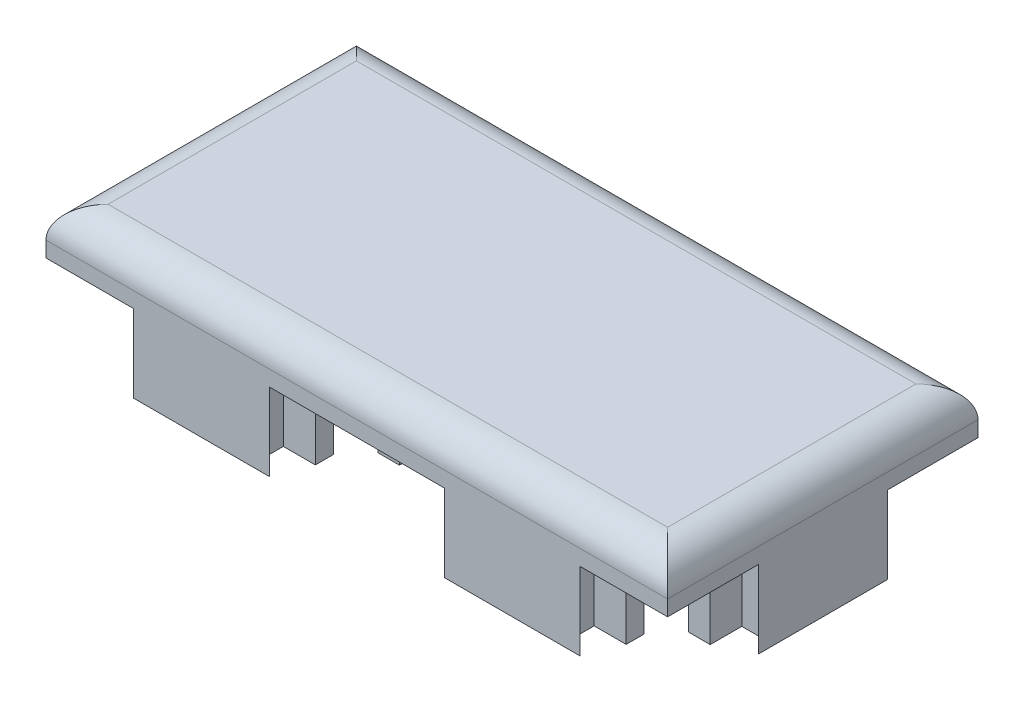
SolidWorks part; units mm, degrees
ref_plane "Alzado" through (0, 0, 0) normal (0, 0, 1) x (1, 0, 0)
ref_plane "Planta" through (0, 0, 0) normal (0, 1, 0) x (1, 0, 0)
ref_plane "Vista lateral" through (0, 0, 0) normal (1, 0, 0) x (0, 0, -1)
sketch "Croquis1" plane through (0, 0, 0) normal (0, 1, 0) x (1, 0, 0)
  line L0 (0, 10) -> (0, -10) construction
  line L1 (-20, -10) -> (20, -10) construction
  line L2 (-20, -10) -> (-20, 10) construction
  line L3 (-20, 10) -> (20, 10) construction
  line L4 (20, -10) -> (20, 10) construction
  line L5 (-20, -10) -> (20, 10) construction
  line L6 (-20, 10) -> (20, -10) construction
  point P0 (0, 0)
  dimension "D1" = 40
  dimension "D2" = 20
sketch "Croquis2" plane through (0, 0, 0) normal (0, 1, 0) x (1, 0, 0)
  line L0 (9.987, 12.4017) -> (9.987, -10.9745) construction
  line L1 (5.615, 10) -> (14.359, 10)
  line L2 (-0.026, 14.7538) -> (-0.026, 4.155) construction
  line L3 (-20, 10) -> (20, 10) construction
  line L4 (4.7752, 6.7111) -> (7.2921, 4.1942)
  line L5 (4.7752, 7.8686) -> (4.7752, 6.7111)
  line L6 (6.8395, 7.8686) -> (4.7752, 7.8686)
  line L7 (6.8395, 8.7755) -> (6.8395, 7.8686)
  line L8 (14.359, 10) -> (13.1345, 8.7755)
  line L9 (13.1345, 8.7755) -> (13.1345, 7.8686)
  line L10 (13.1345, 7.8686) -> (15.1988, 7.8686)
  line L11 (15.1988, 7.8686) -> (15.1988, 6.7111)
  line L12 (15.1988, 6.7111) -> (12.6819, 4.1942)
  line L13 (12.6819, 4.1942) -> (7.2921, 4.1942)
  line L14 (5.615, 10) -> (6.8395, 8.7755)
  line L15 (0, 0) -> (25.8416, 0) construction
  line L16 (20, 4.155) -> (20, -4.155)
  line L17 (-0.026, 4.155) -> (-1.0402, 3.1408)
  line L18 (20, -10) -> (20, 10) construction
  line L19 (20, -4.155) -> (18.9858, -3.1408)
  line L20 (18.9858, -3.1408) -> (17.9195, -3.1408)
  line L21 (17.9195, -3.1408) -> (17.9195, -5.173)
  line L22 (17.9195, -5.173) -> (16.5315, -5.173)
  line L23 (20, 4.155) -> (18.9858, 3.1408)
  line L24 (18.9858, 3.1408) -> (17.9195, 3.1408)
  line L25 (17.9195, 3.1408) -> (17.9195, 5.173)
  line L26 (17.9195, 5.173) -> (16.5315, 5.173)
  line L27 (16.5315, 5.173) -> (14.1751, 2.8166)
  line L28 (14.1751, 2.8166) -> (14.1751, -2.8166)
  line L29 (16.5315, -5.173) -> (14.1751, -2.8166)
  line L30 (4.7752, -6.7111) -> (7.2921, -4.1942)
  line L31 (4.7752, -7.8686) -> (4.7752, -6.7111)
  line L32 (6.8395, -7.8686) -> (4.7752, -7.8686)
  line L33 (6.8395, -8.7755) -> (6.8395, -7.8686)
  line L34 (5.615, -10) -> (6.8395, -8.7755)
  line L35 (5.615, -10) -> (14.359, -10)
  line L36 (14.359, -10) -> (13.1345, -8.7755)
  line L37 (13.1345, -8.7755) -> (13.1345, -7.8686)
  line L38 (13.1345, -7.8686) -> (15.1988, -7.8686)
  line L39 (15.1988, -7.8686) -> (15.1988, -6.7111)
  line L40 (15.1988, -6.7111) -> (12.6819, -4.1942)
  line L41 (12.6819, -4.1942) -> (7.2921, -4.1942)
  line L42 (3.4425, 5.173) -> (5.7989, 2.8166)
  line L43 (5.7989, 2.8166) -> (5.7989, -2.8166)
  line L44 (3.4425, -5.173) -> (5.7989, -2.8166)
  line L45 (2.0545, -5.173) -> (3.4425, -5.173)
  line L46 (2.0545, -3.1408) -> (2.0545, -5.173)
  line L47 (0.9882, -3.1408) -> (2.0545, -3.1408)
  line L48 (-0.026, -4.155) -> (0.9882, -3.1408)
  line L50 (-0.026, 4.155) -> (0.9882, 3.1408)
  line L51 (0.9882, 3.1408) -> (2.0545, 3.1408)
  line L52 (2.0545, 3.1408) -> (2.0545, 5.173)
  line L53 (2.0545, 5.173) -> (3.4425, 5.173)
  line L54 (-0.026, -4.155) -> (-1.0402, -3.1408)
  line L55 (-1.0402, -3.1408) -> (-2.1065, -3.1408)
  line L56 (-1.0402, 3.1408) -> (-2.1065, 3.1408)
  line L57 (-10.039, 12.4017) -> (-10.039, -10.9745) construction
  line L58 (-2.1065, 5.173) -> (-3.4945, 5.173)
  line L59 (-2.1065, 3.1408) -> (-2.1065, 5.173)
  line L60 (-2.1065, -3.1408) -> (-2.1065, -5.173)
  line L61 (-2.1065, -5.173) -> (-3.4945, -5.173)
  line L62 (-3.4945, -5.173) -> (-5.8509, -2.8166)
  line L63 (-5.8509, 2.8166) -> (-5.8509, -2.8166)
  line L64 (-3.4945, 5.173) -> (-5.8509, 2.8166)
  line L65 (-12.7339, -4.1942) -> (-7.3442, -4.1942)
  line L66 (-15.2508, -6.7111) -> (-12.7339, -4.1942)
  line L67 (-15.2508, -7.8686) -> (-15.2508, -6.7111)
  line L68 (-13.1865, -7.8686) -> (-15.2508, -7.8686)
  line L69 (-13.1865, -8.7755) -> (-13.1865, -7.8686)
  line L70 (-14.411, -10) -> (-13.1865, -8.7755)
  line L71 (-5.667, -10) -> (-14.411, -10)
  line L72 (-5.667, -10) -> (-6.8915, -8.7755)
  line L73 (-6.8915, -8.7755) -> (-6.8915, -7.8686)
  line L74 (-6.8915, -7.8686) -> (-4.8272, -7.8686)
  line L75 (-4.8272, -7.8686) -> (-4.8272, -6.7111)
  line L76 (-4.8272, -6.7111) -> (-7.3442, -4.1942)
  line L77 (-16.5836, -5.173) -> (-14.2271, -2.8166)
  line L78 (-14.2271, 2.8166) -> (-14.2271, -2.8166)
  line L79 (-16.5836, 5.173) -> (-14.2271, 2.8166)
  line L80 (-17.9715, 5.173) -> (-16.5836, 5.173)
  line L81 (-17.9715, 3.1408) -> (-17.9715, 5.173)
  line L82 (-19.0378, 3.1408) -> (-17.9715, 3.1408)
  line L83 (-20.052, 4.155) -> (-19.0378, 3.1408)
  line L84 (-17.9715, -5.173) -> (-16.5836, -5.173)
  line L85 (-17.9715, -3.1408) -> (-17.9715, -5.173)
  line L86 (-19.0378, -3.1408) -> (-17.9715, -3.1408)
  line L87 (-20.052, -4.155) -> (-19.0378, -3.1408)
  line L88 (-20.052, 4.155) -> (-20.052, -4.155)
  line L89 (-5.667, 10) -> (-6.8915, 8.7755)
  line L90 (-12.7339, 4.1942) -> (-7.3442, 4.1942)
  line L91 (-15.2508, 6.7111) -> (-12.7339, 4.1942)
  line L92 (-15.2508, 7.8686) -> (-15.2508, 6.7111)
  line L93 (-13.1865, 7.8686) -> (-15.2508, 7.8686)
  line L94 (-13.1865, 8.7755) -> (-13.1865, 7.8686)
  line L95 (-14.411, 10) -> (-13.1865, 8.7755)
  line L96 (-6.8915, 8.7755) -> (-6.8915, 7.8686)
  line L97 (-6.8915, 7.8686) -> (-4.8272, 7.8686)
  line L98 (-4.8272, 7.8686) -> (-4.8272, 6.7111)
  line L99 (-4.8272, 6.7111) -> (-7.3442, 4.1942)
  line L100 (-5.667, 10) -> (-14.411, 10)
  line L101 (-0.026, -4.155) -> (-0.026, -16.1142) construction
  circle A0 centre (-10.039, 0) radius 1.7797
  circle A1 centre (9.987, 0) radius 1.7797
  point P7 (9.987, 4.1942)
  point P18 (9.987, 10)
  point P26 (20, 0)
  point P37 (14.1751, 0)
  point P111 (-14.2271, 0)
  point P112 (-20.052, 0)
  point P113 (-10.039, 10)
  point P114 (-10.039, 4.1942)
extrude "Saliente-Extruir1" add sketch "Croquis2" along normal blind 5
sketch "Croquis3" plane through (0, 5, 0) normal (0, 1, 0) x (1, 0, 0)
  line L0 (-10.039, -10) -> (9.987, -10) construction
  line L1 (-10.039, 10) -> (9.987, 10) construction
  line L2 (-5.667, 10) -> (-14.411, 10) construction
  line L3 (14.359, 10) -> (5.615, 10) construction
  line L4 (-14.411, -10) -> (-5.667, -10) construction
  line L5 (5.615, -10) -> (14.359, -10) construction
  line L6 (-20.052, 0) -> (20, 0) construction
  line L7 (-20.052, 4.155) -> (-20.052, -4.155) construction
  line L8 (20, -4.155) -> (20, 4.155) construction
  line L10 (-20.052, 10) -> (20, 10)
  line L11 (-20.052, 10) -> (-20.052, -10)
  line L12 (-20.052, -10) -> (20, -10)
  line L13 (20, 10) -> (20, -10)
extrude "Saliente-Extruir2" add sketch "Croquis3" along normal blind 3
fillet "Redondeo1" radius 2 4 edges at (-20.052, 8, 0) (-0.026, 8, 10) (20, 8, 0) (-0.026, 8, -10)
